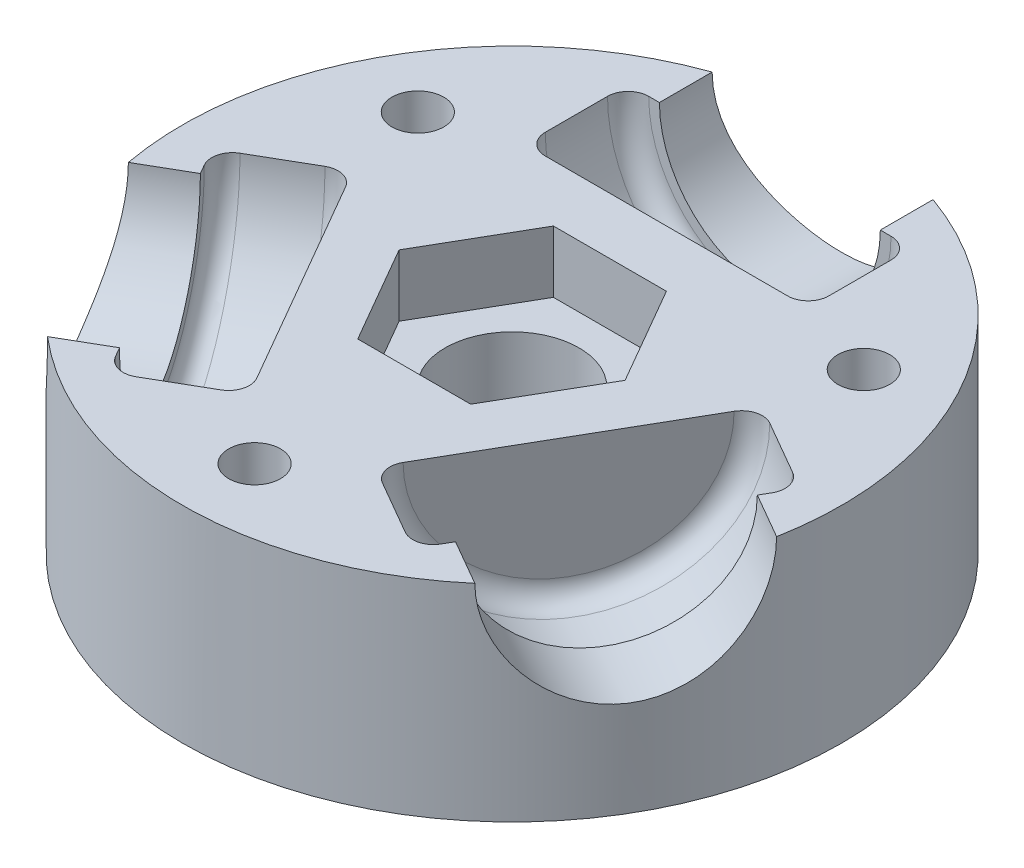
SolidWorks part; units mm, degrees
ref_plane "Front Plane" through (0, 0, 0) normal (0, 0, 1) x (1, 0, 0)
ref_plane "Top Plane" through (0, 0, 0) normal (0, 1, 0) x (1, 0, 0)
ref_plane "Right Plane" through (0, 0, 0) normal (1, 0, 0) x (0, 0, -1)
sketch "Sketch2" plane through (0, 0, 0) normal (0, 1, 0) x (1, 0, 0)
  circle A0 centre (0, 0) radius 32
  dimension "D1" = 64
extrude "Boss-Extrude1" add sketch "Sketch2" along normal blind 20 contours A0
ref_plane "Plane1" through (0, 0, -32) normal (0, 0, -1) x (-1, 0, 0)
sketch "Sketch3" plane through (0, 0, -32) normal (0, 0, -1) x (-1, 0, 0)
  line L0 (32, 20) -> (-32, 20) construction
  circle A0 centre (0, 20) radius 10.725
  dimension "D1" = 21.45
extrude "Cut-Extrude1" cut sketch "Sketch3" against normal blind 6.97 contours A0
ref_plane "Plane2" through (0, 0, -25.03) normal (0, 0, -1) x (-1, 0, 0)
sketch "Sketch4" plane through (0, 0, -25.03) normal (0, 0, -1) x (-1, 0, 0)
  circle A0 centre (0, 20) radius 13.765
  dimension "D1" = 27.53
extrude "Cut-Extrude2" cut sketch "Sketch4" against normal blind 10.04
fillet "Fillet1" radius 2 2 edges at (0, 6.235, -14.99) (0, 6.235, -25.03)
pattern_circular "CirPattern1" count 3 over 360 about axis through (0, 0, 0) along (0, 1, 0) of "Fillet1", "Cut-Extrude2", "Cut-Extrude1"
ref_plane "Plane3" through (0, 20, 0) normal (0, 1, 0) x (1, 0, 0)
sketch "Sketch5" plane through (0, 20, 0) normal (0, 1, 0) x (1, 0, 0)
  circle A0 centre (0, 0) radius 6.5
  dimension "D1" = 13
extrude "Cut-Extrude3" cut sketch "Sketch5" against normal up to surface (20 mm away) up to face at (0, 0, 32)
sketch "Sketch6" plane through (0, 0, 0) normal (0, 1, 0) x (1, 0, 0)
  circle A0 centre (0, 0) radius 17.515
  dimension "D1" = 35.03
extrude "Cut-Extrude4" cut sketch "Sketch6" along normal blind 3 contours A0
sketch "Sketch7" plane through (0, 0, 0) normal (0, 1, 0) x (1, 0, 0)
  circle A0 centre (0, -25) radius 2.515
  circle A1 centre (-21.6506, 12.5) radius 2.515
  circle A2 centre (21.6506, 12.5) radius 2.515
  point P9 (0, 0)
  dimension "D1" = 5.03
  dimension "D2" = 25
  dimension "D3" = 3
extrude "Cut-Extrude5" cut sketch "Sketch7" along normal up to surface (20 mm away) up to face at (0, 20, 6.5)
sketch "Sketch8" plane through (0, 20, 0) normal (0, 1, 0) x (1, 0, 0)
  line L0 (11.765, 14.99) -> (-11.765, 14.99) construction
  line L1 (5.4848, 9.5) -> (-5.4848, 9.5)
  line L2 (-5.4848, 9.5) -> (-10.9697, 0)
  line L3 (-10.9697, 0) -> (-5.4848, -9.5)
  line L4 (-5.4848, -9.5) -> (5.4848, -9.5)
  line L5 (5.4848, -9.5) -> (10.9697, 0)
  line L6 (10.9697, 0) -> (5.4848, 9.5)
  circle A0 centre (0, 0) radius 9.5 construction
  point P1 (5.5192, -9.4801)
  point P10 (0, 0)
  dimension "D1" = 19
extrude "Cut-Extrude6" cut sketch "Sketch8" against normal blind 6
